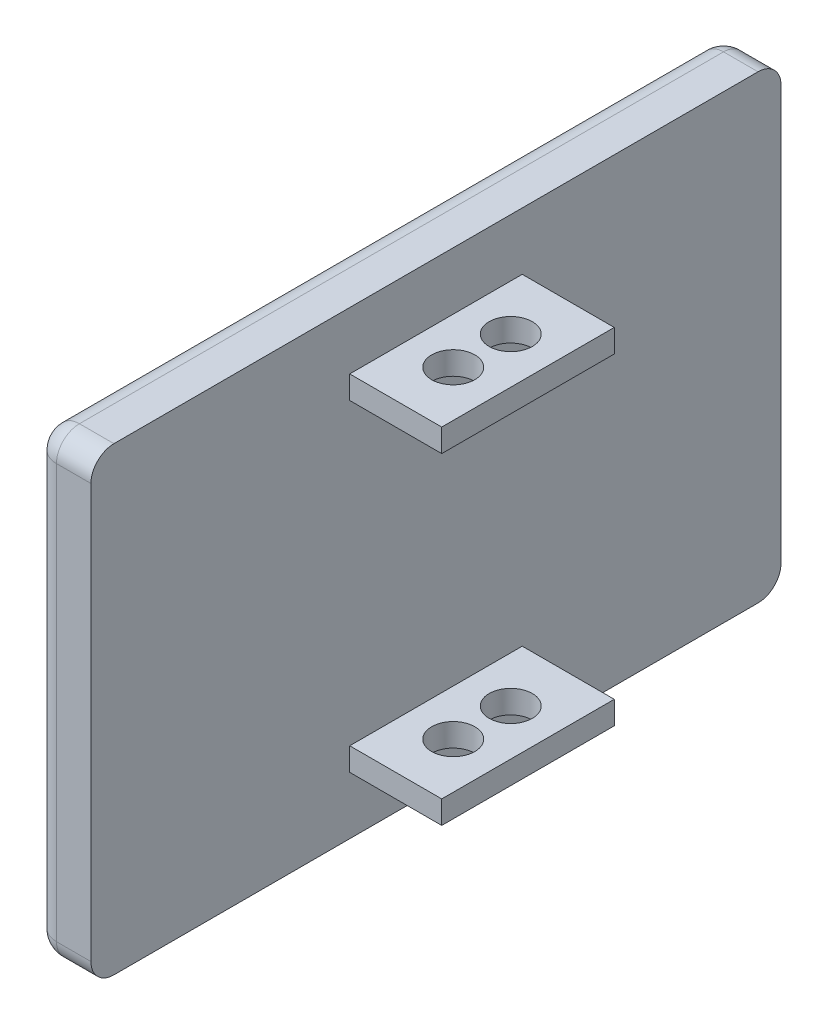
SolidWorks part; units mm, degrees
material "6061-T6 (SS)"
ref_plane "X-Y Datum" through (0, 0, 0) normal (0, 0, 1) x (1, 0, 0)
ref_plane "X-Z Datum" through (0, 0, 0) normal (0, 1, 0) x (1, 0, 0)
ref_plane "Y-Z Datum" through (0, 0, 0) normal (1, 0, 0) x (0, 0, -1)
sketch "Sketch1" plane through (0, 0, 0) normal (1, 0, 0) x (0, 0, -1)
  line L1 (38.1, -25.4) -> (-38.1, -25.4)
  line L2 (38.1, -25.4) -> (38.1, 25.4)
  line L3 (38.1, 25.4) -> (-38.1, 25.4)
  line L4 (-38.1, -25.4) -> (-38.1, 25.4)
  line L5 (38.1, -25.4) -> (-38.1, 25.4) construction
  line L6 (38.1, 25.4) -> (-38.1, -25.4) construction
  point P0 (0, 0)
  dimension "D1" = 50.8
  dimension "D2" = 76.2
extrude "Boss-Extrude1" add sketch "Sketch1" along normal blind 6.35
sketch "Sketch2" plane through (6.35, 0, 0) normal (1, 0, 0) x (0, 0, -1)
  line L0 (-38.1, 25.4) -> (-38.1, -25.4) construction
  line L1 (-9.525, -19.05) -> (9.525, -19.05)
  line L2 (-9.525, -19.05) -> (-9.525, -16.51)
  line L3 (-9.525, -16.51) -> (9.525, -16.51)
  line L4 (9.525, -19.05) -> (9.525, -16.51)
  line L5 (38.1, -25.4) -> (38.1, 25.4) construction
  line L6 (-38.1, 0) -> (38.1, 0) construction
  line L7 (-9.525, 16.51) -> (9.525, 16.51)
  line L8 (9.525, 19.05) -> (9.525, 16.51)
  line L9 (-9.525, 19.05) -> (9.525, 19.05)
  line L10 (-9.525, 19.05) -> (-9.525, 16.51)
  point P16 (0, -16.51)
  point P17 (0, 0)
  dimension "D1" = 2.54
  dimension "D2" = 16.51
  dimension "D3" = 19.05
extrude "Boss-Extrude2" add sketch "Sketch2" along normal blind 10.16
fillet "Fillet1" radius 2.54 8 edges at (3.175, 25.4, -38.1) (3.175, -25.4, -38.1) (3.175, -25.4, 38.1) (3.175, 25.4, 38.1) (0, -25.4, 0) (0, 0, -38.1) (0, 25.4, 0) (0, 0, 38.1)
sketch "Sketch3" plane through (0, 19.05, 0) normal (0, 1, 0) x (1, 0, 0)
  line L1 (6.35, 9.525) -> (6.35, -9.525) construction
  line L2 (11.43, -3.175) -> (11.43, 3.175) construction
  line L4 (11.43, 0) -> (16.51, 0) construction
  line L5 (16.51, 9.525) -> (16.51, -9.525) construction
  circle A0 centre (11.43, -3.175) radius 2.3813
  circle A1 centre (11.43, 3.175) radius 2.3813
  dimension "D1" = 4.7625
  dimension "D3" = 5.08
  dimension "D2" = 6.35
extrude "Cut-Extrude1" cut sketch "Sketch3" against normal up to surface (38.1 mm away) up to face at (11.43, -19.05, 0)
